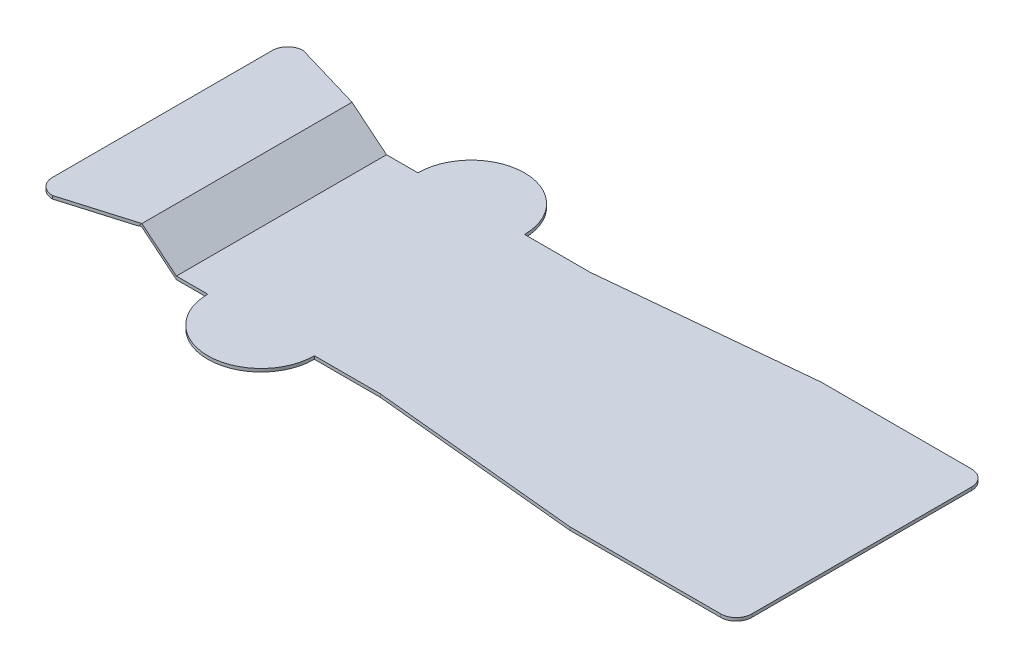
SolidWorks part; units mm, degrees
ref_plane "정면" through (0, 0, 0) normal (0, 0, 1) x (1, 0, 0)
ref_plane "윗면" through (0, 0, 0) normal (0, 1, 0) x (1, 0, 0)
ref_plane "우측면" through (0, 0, 0) normal (1, 0, 0) x (0, 0, -1)
sketch "스케치1" plane through (0, 0, 0) normal (0, 1, 0) x (1, 0, 0)
  line L1 (-111.5, 40) -> (111.5, 40)
  line L2 (-111.5, 40) -> (-111.5, -40)
  line L3 (-111.5, -40) -> (111.5, -40)
  line L4 (111.5, 40) -> (111.5, -40)
  line L5 (-111.5, 40) -> (111.5, -40) construction
  line L6 (-111.5, -40) -> (111.5, 40) construction
  point P0 (0, 0)
  dimension "D1" = 223
  dimension "D2" = 80
extrude "보스-돌출1" add sketch "스케치1" along normal blind 10
sketch "스케치3" plane through (0, 0, 40) normal (0, 0, 1) x (1, 0, 0)
  line L0 (-111.5, 10) -> (-111.5, 9)
  line L1 (-111.5, 10) -> (-111.5, 0) construction
  line L2 (-111.5, 9) -> (-84.5, 9)
  line L3 (111.5, 0) -> (-73.5, 0)
  line L4 (-111.5, 0) -> (111.5, 0) construction
  line L5 (-84.5, 9) -> (-73.5, 0)
  line L6 (111.5, 0) -> (111.5, 1)
  line L7 (111.5, 10) -> (111.5, 0) construction
  line L8 (-111.5, 10) -> (-84.5, 10)
  line L9 (-111.5, 10) -> (111.5, 10) construction
  line L10 (-73.5, 0) -> (-73.5, 1) construction
  line L11 (-84.5, 10) -> (-73.5, 1)
  line L12 (-73.5, 1) -> (111.5, 1)
  dimension "D1" = 1
  dimension "D2" = 27
  dimension "D3" = 185
  dimension "D4" = 1
  dimension "D5" = 1
extrude "컷-돌출1" cut sketch "스케치3" against normal through all flip side to cut
sketch "스케치5" plane through (0, 10, 0) normal (0, 1, 0) x (1, 0, 0)
  line L0 (-111.5, 0) -> (-84.5, 0) construction
  line L1 (-111.5, 40) -> (-111.5, -40) construction
  line L2 (-84.5, 40) -> (-84.5, -40) construction
  line L3 (-84.5, 40) -> (-111.5, 40) construction
  line L4 (-111.5, 35.0293) -> (-111.5, 40)
  line L5 (-111.5, -35.0293) -> (-111.5, -40)
  line L6 (-111.5, 40) -> (-106.5293, 40)
  line L7 (-111.5, -40) -> (-106.5293, -40)
  circle A1 centre (-106.5293, 35.0293) radius 4.9707
  circle A2 centre (-106.5293, -35.0293) radius 4.9707
  line M4 (-111.5, -40) -> (-84.5, -40)
  line M6 (-84.5, 40) -> (-111.5, 40)
  line M7 (-111.5, 40) -> (-111.5, -40)
extrude "컷-돌출2" cut sketch "스케치5" against normal through all contours A1 M6 M7 | A2 M4 M7
sketch "스케치6" plane through (0, 10, 0) normal (0, 1, 0) x (1, 0, 0)
  line L0 (-84.5, 33.5) -> (-106.5293, 40)
  line L2 (-84.5, -33.5) -> (-84.5, 33.5)
  line L3 (-84.5, 40) -> (-84.5, -40) construction
  line L4 (-106.5293, -40) -> (-84.5, -33.5)
  line L5 (-84.5, 33.5) -> (-84.5, 40)
  line L6 (-84.5, 40) -> (-106.5293, 40)
  line L7 (-84.5, -33.5) -> (-84.5, -40)
  line L8 (-84.5, -40) -> (-106.5293, -40)
  point P10 (-84.5, 0)
  line M3 (-84.5, 40) -> (-106.5293, 40)
  line M7 (-106.5293, -40) -> (-84.5, -40)
  line M8 (-84.5, -40) -> (-84.5, 40)
  dimension "D1" = 67
extrude "컷-돌출3" cut sketch "스케치6" against normal through all contours L0 M8 M3 | L4 M7 M8
sketch "스케치7" plane through (-28.9827, -35.4233, 0) normal (0.6332, 0.774, 0) x (0.774, -0.6332, 0)
  line L0 (-71.7318, 0) -> (-57.5191, 0) construction
  line L5 (-71.7318, 33.5) -> (-71.7318, -33.5) construction
  line L6 (-57.5191, 40) -> (-57.5191, -40) construction
  line L7 (-71.7318, -40) -> (-71.7318, -33.5)
  line L8 (-71.7318, 40) -> (-57.5191, 40)
  line L9 (-71.7318, 40) -> (-71.7318, 33.5)
  line L10 (-71.7318, 33.5) -> (-57.5191, 33.5)
  line L11 (-57.5191, 40) -> (-57.5191, 33.5)
  line L12 (-71.7318, -40) -> (-57.5191, -40)
  line L13 (-57.5191, -40) -> (-57.5191, -33.5)
  line L14 (-71.7318, -33.5) -> (-57.5191, -33.5)
extrude "컷-돌출4" cut sketch "스케치7" against normal through all
sketch "스케치9" plane through (0, 1, 0) normal (0, 1, 0) x (1, 0, 0)
  line L0 (-73.5, 0) -> (111.5, 0) construction
  line L1 (-73.5, 33.5) -> (-73.5, -33.5) construction
  line L2 (111.5, 40) -> (111.5, -40) construction
  line L12 (111.5, 40) -> (-73.5, 40) construction
  line L13 (-73.5, 33.5) -> (-8.5, 33.5)
  line L14 (-73.5, 33.5) -> (-73.5, 40)
  line L15 (-73.5, 40) -> (-8.5, 40)
  line L16 (-8.5, 33.5) -> (-8.5, 40)
  line L17 (-73.5, -33.5) -> (-73.5, -40)
  line L18 (-73.5, -33.5) -> (-8.5, -33.5)
  line L19 (-8.5, -33.5) -> (-8.5, -40)
  line L20 (-73.5, -40) -> (-8.5, -40)
  dimension "D1" = 65
extrude "컷-돌출6" cut sketch "스케치9" against normal through all
sketch "스케치10" plane through (-29.4728, -36.0223, 0) normal (-0.6332, -0.774, 0) x (0.774, -0.6332, 0)
  line L0 (-71.0985, 0) -> (-56.8859, 0) construction
  line L1 (-71.0985, -33.5) -> (-71.0985, 33.5) construction
  line L2 (-56.8859, -33.5) -> (-56.8859, 33.5) construction
  line L3 (-57.5191, -40) -> (-57.5191, -33.5)
  line L4 (-57.5191, 40) -> (-56.8859, 40)
  line L5 (-57.5191, 40) -> (-57.5191, 33.5)
  line L6 (-57.5191, 33.5) -> (-56.8859, 33.5)
  line L7 (-56.8859, 40) -> (-56.8859, 33.5)
  line L8 (-57.5191, -40) -> (-56.8859, -40)
  line L9 (-56.8859, -40) -> (-56.8859, -33.5)
  line L10 (-57.5191, -33.5) -> (-56.8859, -33.5)
extrude "컷-돌출7" cut sketch "스케치10" against normal through all
sketch "스케치11" plane through (0, 1, 0) normal (0, 1, 0) x (1, 0, 0)
  line L0 (111.5, -40) -> (-8.5, -40) construction
  line L1 (111.5, 40) -> (58.5, 40)
  line L2 (111.5, 40) -> (111.5, -40)
  line L3 (111.5, -40) -> (58.5, -40)
  line L4 (58.5, 40) -> (58.5, -40)
  line L5 (111.5, 0) -> (-111.5, 0) construction
  line L6 (-111.5, 35.0293) -> (-111.5, -35.0293) construction
  line L7 (-8.5, -33.5) -> (-8.5, -40)
  line L8 (-8.5, 33.5) -> (-8.5, 40)
  line L9 (-8.5, -40) -> (58.5, -40)
  line L10 (-8.5, 40) -> (58.5, 40)
  line L11 (-8.5, -33.5) -> (58.5, -40)
  line L12 (-8.5, 33.5) -> (58.5, 40)
  line M1 (-8.5, 40) -> (-8.5, 33.5)
  line M5 (-8.5, -33.5) -> (-8.5, -40)
  line M6 (-8.5, -40) -> (111.5, -40)
  line M8 (111.5, 40) -> (-8.5, 40)
  dimension "D1" = 53
extrude "컷-돌출8" cut sketch "스케치11" against normal through all contours L11 M5 M6 | L12 M1 M8
sketch "스케치12" plane through (0, 1, 0) normal (0, 1, 0) x (1, 0, 0)
  line L0 (-111.5, 0) -> (111.5, 0) construction
  line L1 (-111.5, 35.0293) -> (-111.5, -35.0293) construction
  line L2 (111.5, 40) -> (111.5, -40) construction
  line L3 (111.5, 40) -> (58.5, 40) construction
  line L4 (106.53, 40) -> (111.5, 40)
  line L5 (106.53, -40) -> (111.5, -40)
  line L6 (111.5, 40) -> (111.5, 35.03)
  line L7 (111.5, -40) -> (111.5, -35.03)
  circle A0 centre (106.53, 35.03) radius 4.97
  circle A1 centre (106.53, -35.03) radius 4.97
  line M4 (58.5, -40) -> (111.5, -40)
  line M5 (111.5, -40) -> (111.5, 40)
  line M6 (111.5, 40) -> (58.5, 40)
  dimension "D1" = 9.94
extrude "컷-돌출9" cut sketch "스케치12" against normal through all contours A0 M5 M6 | A1 M5 M4
sketch "스케치13" plane through (0, 1, 0) normal (0, 1, 0) x (1, 0, 0)
  line L0 (-111.5, 0) -> (111.5, 0) construction
  line L1 (-111.5, 35.0293) -> (-111.5, -35.0293) construction
  line L2 (111.5, 35.03) -> (111.5, -35.03) construction
  line L3 (-73.5, -33.5) -> (-63.5, -33.5) construction
  line L4 (-8.5, -33.5) -> (-73.5, -33.5) construction
  line L5 (-73.5, 33.5) -> (-63.5, 33.5) construction
  line L6 (-63.5, 47.0926) -> (-63.5, -50.3127)
  line L7 (-63.5, -47.0926) -> (-63.5, 50.3127)
  circle A2 centre (-46.5, -33.5) radius 17
  circle A3 centre (-46.5, 33.5) radius 17
  line M6 (-8.5, 33.5) -> (-73.5, 33.5)
  line M8 (-73.5, -33.5) -> (-8.5, -33.5)
  dimension "D1" = 34
extrude "보스-돌출2" add sketch "스케치13" against normal blind 1 contours A3 M6 | A2 M8
